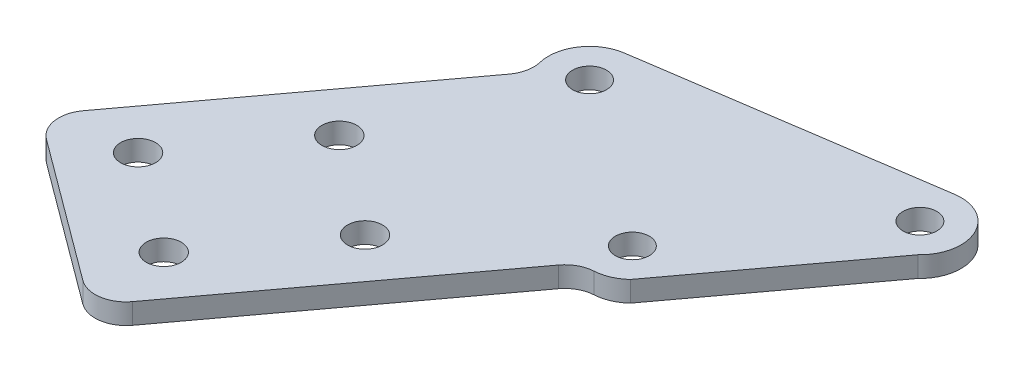
SolidWorks part; units mm, degrees
ref_plane "Front Plane" through (0, 0, 0) normal (0, 0, 1) x (1, 0, 0)
ref_plane "Top Plane" through (0, 0, 0) normal (0, 1, 0) x (1, 0, 0)
ref_plane "Right Plane" through (0, 0, 0) normal (1, 0, 0) x (0, 0, -1)
sketch "Sketch1" plane through (0, 0, 0) normal (0, 1, 0) x (1, 0, 0)
  line L0 (1.4975, 0.7868) -> (-36.9339, 98.5008) construction
  line L6 (-56.6569, 90.4835) -> (-36.9937, 86.8285) construction
  line L17 (-34.7298, 79.5308) -> (-58.048, 63.5226) construction
  line L18 (-61.6543, 88.9381) -> (-90.7933, 94.3545) construction
  line L19 (1.4975, 0.7868) -> (79.9099, 31.6269) construction
  line L20 (-94.291, 91.9533) -> (-97.3978, 75.2396) construction
  line L21 (-65.8576, 66.3255) -> (-94.9966, 71.7418) construction
  line L22 (6.159, 94.65) -> (23.8009, 118.4656) construction
  line L23 (9.5157, 132.7811) -> (23.176, 122.6619) construction
  line L24 (-12.3225, 108.3406) -> (5.3194, 132.1562) construction
  line L25 (-25.6246, 83.1119) -> (2.3512, 87.278) construction
  line L26 (-17.0338, 106.0675) -> (-28.9387, 89.9966) construction
  line L27 (59.6519, -88.9099) -> (39.9887, -85.2549) construction
  line L28 (37.7248, -77.9572) -> (61.043, -61.949) construction
  line L29 (64.6494, -87.3645) -> (93.7884, -92.7809) construction
  line L30 (97.2861, -90.3797) -> (100.3929, -73.666) construction
  line L31 (68.8527, -64.7518) -> (97.9916, -70.1682) construction
  line L32 (-3.1639, -93.0764) -> (-20.8058, -116.8919)
  line L33 (-6.5207, -131.2074) -> (-20.1809, -121.0883)
  line L34 (15.3176, -106.767) -> (-2.3243, -130.5825)
  line L35 (28.6196, -81.5383) -> (0.6438, -85.7043)
  line L36 (20.0288, -104.4939) -> (31.9337, -88.423)
  circle A33 centre (-56.6569, 86.4835) radius 1.65 construction
  circle A34 centre (-36.9937, 82.8285) radius 1.65 construction
  circle A35 centre (-40.6487, 63.1653) radius 1.65 construction
  circle A36 centre (-60.3119, 66.8203) radius 1.65 construction
  arc A37 (-56.6569, 90.4835) -> (-59.1993, 89.5716) centre (-56.6569, 86.4835) ccw construction
  arc A38 (-34.7298, 79.5308) -> (-36.9937, 86.8285) centre (-36.9937, 82.8285) ccw construction
  arc A39 (-63.7941, 64.8521) -> (-58.048, 63.5226) centre (-60.3119, 66.8203) ccw construction
  arc A40 (-65.8576, 66.3255) -> (-63.7941, 64.8521) centre (-66.4058, 63.376) cw construction
  arc A41 (-59.1993, 89.5716) -> (-61.6543, 88.9381) centre (-61.1061, 91.8876) cw construction
  arc A42 (-90.7933, 94.3545) -> (-94.291, 91.9533) centre (-91.3416, 91.405) ccw construction
  arc A43 (-94.9966, 71.7418) -> (-97.3978, 75.2396) centre (-94.4483, 74.6913) cw construction
  arc A44 (23.8009, 118.4656) -> (23.176, 122.6619) centre (21.3903, 120.2513) ccw construction
  arc A45 (5.3194, 132.1562) -> (9.5157, 132.7811) centre (7.73, 130.3704) cw construction
  arc A46 (-14.5513, 107.1319) -> (-12.3225, 108.3406) centre (-14.7332, 110.1263) ccw construction
  arc A47 (6.159, 94.65) -> (5.6521, 92.1657) centre (8.5696, 92.8643) ccw construction
  arc A48 (5.6521, 92.1657) -> (2.3512, 87.278) centre (1.7621, 91.2343) cw construction
  arc A49 (-25.6246, 83.1119) -> (-28.9387, 89.9966) centre (-26.2137, 87.0683) cw construction
  arc A50 (-17.0338, 106.0675) -> (-14.5513, 107.1319) centre (-14.3088, 103.1392) cw construction
  circle A51 centre (1.7621, 91.2343) radius 1.65 construction
  circle A52 centre (-10.1428, 75.1634) radius 1.65 construction
  circle A53 centre (-26.2137, 87.0683) radius 1.65 construction
  circle A54 centre (-14.3088, 103.1392) radius 1.65 construction
  circle A55 centre (59.6519, -84.9099) radius 1.65 construction
  circle A56 centre (39.9887, -81.2549) radius 1.65 construction
  circle A57 centre (43.6437, -61.5917) radius 1.65 construction
  circle A58 centre (63.3069, -65.2467) radius 1.65 construction
  arc A59 (59.6519, -88.9099) -> (62.1943, -87.9979) centre (59.6519, -84.9099) ccw construction
  arc A60 (37.7248, -77.9572) -> (39.9887, -85.2549) centre (39.9887, -81.2549) ccw construction
  arc A61 (66.7892, -63.2785) -> (61.043, -61.949) centre (63.3069, -65.2467) ccw construction
  arc A62 (68.8527, -64.7518) -> (66.7892, -63.2785) centre (69.4009, -61.8024) cw construction
  arc A63 (62.1943, -87.9979) -> (64.6494, -87.3645) centre (64.1012, -90.314) cw construction
  arc A64 (93.7884, -92.7809) -> (97.2861, -90.3797) centre (94.3366, -89.8314) ccw construction
  arc A65 (97.9916, -70.1682) -> (100.3929, -73.666) centre (97.4434, -73.1177) cw construction
  arc A66 (-20.8058, -116.8919) -> (-20.1809, -121.0883) centre (-18.3952, -118.6777) ccw
  arc A67 (-2.3243, -130.5825) -> (-6.5207, -131.2074) centre (-4.7349, -128.7968) cw
  arc A68 (17.5464, -105.5582) -> (15.3176, -106.767) centre (17.7282, -108.5527) ccw
  arc A69 (-3.1639, -93.0764) -> (-2.657, -90.5921) centre (-5.5746, -91.2907) ccw
  arc A70 (-2.657, -90.5921) -> (0.6438, -85.7043) centre (1.233, -89.6607) cw
  arc A71 (28.6196, -81.5383) -> (31.9337, -88.423) centre (29.2088, -85.4947) cw
  arc A72 (20.0288, -104.4939) -> (17.5464, -105.5582) centre (17.3039, -101.5656) cw
  circle A73 centre (1.233, -89.6607) radius 1.65
  circle A74 centre (13.1379, -73.5898) radius 1.65 construction
  circle A75 centre (29.2088, -85.4947) radius 1.65
  circle A76 centre (17.3039, -101.5656) radius 1.65
  dimension "D1" = 8
  dimension "D2" = 8
  dimension "D3" = 8
  dimension "D4" = 3
  dimension "D5" = 3
extrude "Boss-Extrude1" add sketch "Sketch1" along normal mid plane 2
sketch "Sketch9" plane through (0, 1, 0) normal (0, 1, 0) x (1, 0, 0)
  line L0 (-14.6006, -117.7551) -> (-4.9581, -124.8981) construction
  line L1 (-20.1809, -121.0883) -> (-6.5207, -131.2074) construction
  line L2 (-6.2672, -106.5055) -> (3.3753, -113.6484) construction
  line L3 (-2.3243, -130.5825) -> (15.3176, -106.767) construction
  circle A0 centre (-6.2672, -106.5055) radius 1.7
  circle A1 centre (-14.6006, -117.7551) radius 1.7
  circle A2 centre (-4.9581, -124.8981) radius 1.7
  circle A3 centre (3.3753, -113.6484) radius 1.7
  dimension "D7" = 3.4
  dimension "D1" = 14
  dimension "D2" = 6
  dimension "D3" = 5.5
  dimension "D4" = 5.5
  dimension "D5" = 12
  dimension "D6" = 12
extrude "Cut-Extrude3" cut sketch "Sketch9" against normal blind 2
